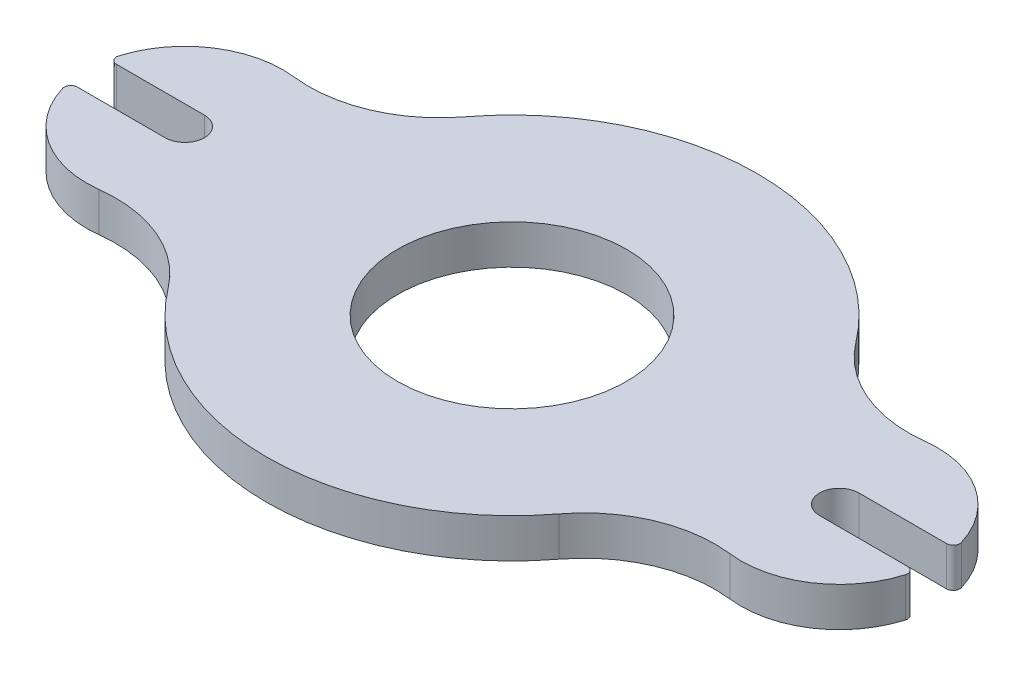
SolidWorks part; units mm, degrees
ref_plane "Front Plane" through (0, 0, 0) normal (0, 0, 1) x (1, 0, 0)
ref_plane "Top Plane" through (0, 0, 0) normal (0, 1, 0) x (1, 0, 0)
ref_plane "Right Plane" through (0, 0, 0) normal (1, 0, 0) x (0, 0, -1)
sketch "Sketch1" plane through (0, 0, 0) normal (0, 1, 0) x (1, 0, 0)
  line L0 (-55, 0) -> (55, 0) construction
  line L1 (0, -55) -> (0, 55) construction
  line L2 (50, -3) -> (63.4164, -3)
  line L3 (-50, 3) -> (-63.4164, 3)
  line L5 (-50, -3) -> (-63.4164, -3)
  line L7 (50, 3) -> (63.4164, 3)
  circle A0 centre (0, 0) radius 17.5
  arc A2 (-50, -3) -> (-50, 3) centre (-50, 0) ccw
  arc A3 (-29.8777, -22.6621) -> (29.8777, -22.6621) centre (0, 0) ccw
  arc A4 (-48.2054, 14.8923) -> (-64.3747, 4.2857) centre (-50, 0) ccw
  arc A5 (48.2054, 14.8923) -> (64.3747, 4.2857) centre (50, 0) cw
  arc A6 (50, -3) -> (50, 3) centre (50, 0) cw
  arc A7 (29.8777, 22.6621) -> (-29.8777, 22.6621) centre (0, 0) ccw
  arc A8 (29.8777, -22.6621) -> (48.2054, -14.8923) centre (45.8125, -34.7486) cw
  arc A9 (48.2054, 14.8923) -> (29.8777, 22.6621) centre (45.8125, 34.7486) cw
  arc A10 (-29.8777, -22.6621) -> (-48.2054, -14.8923) centre (-45.8125, -34.7486) ccw
  arc A11 (-29.8777, 22.6621) -> (-48.2054, 14.8923) centre (-45.8125, 34.7486) cw
  arc A12 (-64.3747, -4.2857) -> (-48.2054, -14.8923) centre (-50, 0) ccw
  arc A13 (64.3747, -4.2857) -> (48.2054, -14.8923) centre (50, 0) cw
  arc A14 (64.3747, 4.2857) -> (63.4164, 3) centre (63.4164, 4) cw
  arc A15 (63.4164, -3) -> (64.3747, -4.2857) centre (63.4164, -4) cw
  arc A16 (-63.4164, -3) -> (-64.3747, -4.2857) centre (-63.4164, -4) ccw
  arc A17 (-64.3747, 4.2857) -> (-63.4164, 3) centre (-63.4164, 4) ccw
  point P19 (36.8125, 7.1477)
  point P32 (64.6969, 3)
  point P35 (64.6969, -3)
  point P38 (-64.6969, -3)
  point P41 (-64.6969, 3)
  dimension "D1" = 35
  dimension "D2" = 20
  dimension "D3" = 6
  dimension "D5" = 1
  dimension "D6" = 20
  dimension "D7" = 15
  dimension "D4" = 50
extrude "Boss-Extrude1" add sketch "Sketch1" along normal blind 6
pattern_circular "CirPattern1" [suppressed] count 6 over 360
